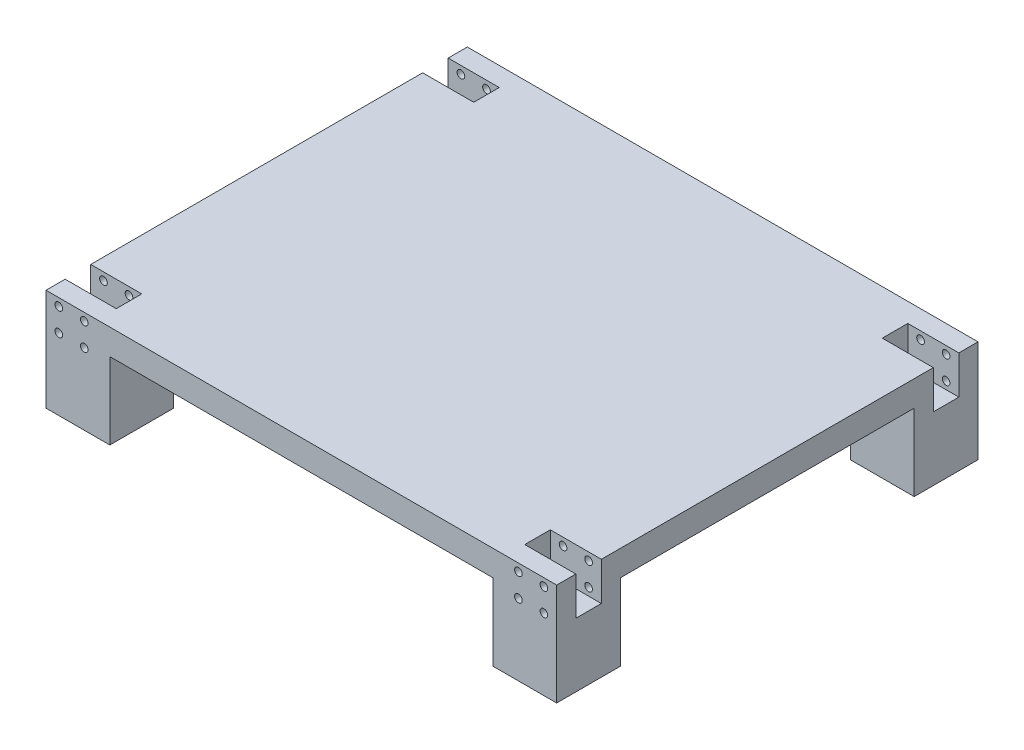
SolidWorks part; units mm, degrees
ref_plane "前视基准面" through (0, 0, 0) normal (0, 0, 1) x (1, 0, 0)
ref_plane "上视基准面" through (0, 0, 0) normal (0, 1, 0) x (1, 0, 0)
ref_plane "右视基准面" through (0, 0, 0) normal (1, 0, 0) x (0, 0, -1)
sketch "草图3" plane through (0, 0, 0) normal (0, 1, 0) x (1, 0, 0)
  line L1 (-100, -82.5) -> (100, -82.5)
  line L2 (-100, -82.5) -> (-100, 82.5)
  line L3 (-100, 82.5) -> (100, 82.5)
  line L4 (100, -82.5) -> (100, 82.5)
  line L5 (-100, -82.5) -> (100, 82.5) construction
  line L6 (-100, 82.5) -> (100, -82.5) construction
  point P0 (0, 0)
  dimension "D1" = 200
  dimension "D2" = 165
extrude "凸台-拉伸1" add sketch "草图3" against normal blind 10
sketch "草图4" plane through (0, -10, 0) normal (0, -1, 0) x (1, 0, 0)
  line L1 (-100, 82.5) -> (-75, 82.5)
  line L2 (-100, 82.5) -> (-100, 57.5)
  line L3 (-100, 57.5) -> (-75, 57.5)
  line L4 (-75, 82.5) -> (-75, 57.5)
  line L5 (100, 82.5) -> (75, 82.5)
  line L6 (100, 82.5) -> (100, 57.5)
  line L7 (100, 57.5) -> (75, 57.5)
  line L8 (75, 82.5) -> (75, 57.5)
  line L9 (-100, -82.5) -> (-75, -82.5)
  line L10 (-100, -82.5) -> (-100, -57.5)
  line L11 (-100, -57.5) -> (-75, -57.5)
  line L12 (-75, -82.5) -> (-75, -57.5)
  line L13 (100, -82.5) -> (75, -82.5)
  line L14 (100, -82.5) -> (100, -57.5)
  line L15 (100, -57.5) -> (75, -57.5)
  line L16 (75, -82.5) -> (75, -57.5)
  dimension "D1" = 25
  dimension "D2" = 25
  dimension "D3" = 25
  dimension "D4" = 25
  dimension "D5" = 25
  dimension "D6" = 25
  dimension "D7" = 25
  dimension "D8" = 25
extrude "凸台-拉伸2" add sketch "草图4" along normal blind 30
sketch "草图5" plane through (0, 0, 0) normal (0, 1, 0) x (1, 0, 0)
  line L0 (-100, 82.5) -> (-100, -82.5) construction
  line L1 (-100, 75) -> (-80, 75)
  line L2 (-100, 75) -> (-100, 65)
  line L3 (-100, 65) -> (-80, 65)
  line L4 (-80, 75) -> (-80, 65)
  line L5 (100, -82.5) -> (100, 82.5) construction
  line L6 (-100, -62.6088) -> (-56.8762, -62.6088)
  line L7 (-100, -62.6088) -> (-100, -70.9267)
  line L8 (-100, -70.9267) -> (-56.8762, -70.9267)
  line L9 (-56.8762, -62.6088) -> (-56.8762, -70.9267)
  line L10 (100, 67.1049) -> (61.1476, 67.1049)
  line L11 (100, 67.1049) -> (100, 59.0119)
  line L12 (100, 59.0119) -> (61.1476, 59.0119)
  line L13 (61.1476, 67.1049) -> (61.1476, 59.0119)
  line L14 (100, 82.5) -> (-100, 82.5) construction
  line L15 (100, -62.6088) -> (59.3491, -62.6088)
  line L16 (100, -62.6088) -> (100, -70.9267)
  line L17 (100, -70.9267) -> (59.3491, -70.9267)
  line L18 (59.3491, -62.6088) -> (59.3491, -70.9267)
  line M11 (-100, 82.5) -> (-100, -82.5)
  dimension "D1" = 7.5
  dimension "D2" = 10
  dimension "D3" = 20
extrude "切除-拉伸2" cut sketch "草图5" against normal blind 15 contours L4 L1 L3 M11
mirror "镜向1" about plane through (0, 0, 0) normal (0, 0, 1) of "切除-拉伸2"
mirror "镜向2" about plane through (0, 0, 0) normal (1, 0, 0) of "镜向1", "切除-拉伸2"
sketch "草图6" plane through (0, 0, 82.5) normal (0, 0, 1) x (1, 0, 0)
  line L0 (-100, 0) -> (100, 0) construction
  line L1 (-100, -40) -> (-100, 0) construction
  circle A0 centre (-95, -3) radius 1.5
  circle A1 centre (-85, -3) radius 1.5
  circle A2 centre (-95, -12) radius 1.5
  circle A3 centre (-85, -12) radius 1.5
  dimension "D1" = 3
  dimension "D2" = 3
  dimension "D3" = 3
  dimension "D4" = 3
  dimension "D5" = 3
  dimension "D6" = 3
  dimension "D7" = 9
  dimension "D8" = 0
  dimension "D9" = 9
  dimension "D10" = 5
  dimension "D11" = 10
extrude "切除-拉伸3" cut sketch "草图6" against normal blind 20
mirror "镜向3" about plane through (0, 0, 0) normal (0, 0, 1) of "切除-拉伸3"
mirror "镜向4" about plane through (0, 0, 0) normal (1, 0, 0) of "镜向3", "切除-拉伸3"
